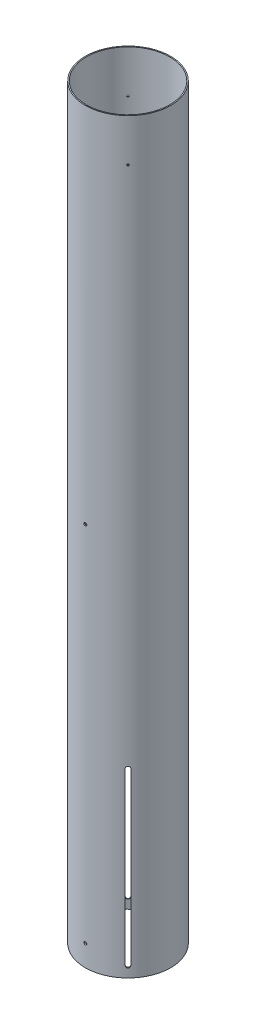
SolidWorks part; units mm, degrees
material "Wildman Fiberglass"
ref_plane "Front Plane" through (0, 0, 0) normal (0, 0, 1) x (1, 0, 0)
ref_plane "Top Plane" through (0, 0, 0) normal (0, 1, 0) x (1, 0, 0)
ref_plane "Right Plane" through (0, 0, 0) normal (1, 0, 0) x (0, 0, -1)
sketch "Sketch1" plane through (0, 0, 0) normal (0, 1, 0) x (1, 0, 0)
  circle A0 centre (0, 0) radius 49.53
  circle A1 centre (0, 0) radius 50.8
  dimension "D1" = 101.6
  dimension "D2" = 99.06
extrude "Boss-Extrude1" add sketch "Sketch1" along normal blind 889
extrude "Cut-Extrude1" cut sketch "Sketch2" against normal blind 152.4
sketch "Sketch2" plane through (14.4921, 1243.3556, -192.6285) normal (0.7071, 0, -0.7071) x (0, 1, 0)
  line L0 (-1230.6556, 128.3427) -> (-1027.4556, 128.3427)
  line L1 (-1027.4556, 123.5802) -> (-1230.6556, 123.5802)
  arc A0 (-1230.6556, 128.3427) -> (-1230.6556, 123.5802) centre (-1230.6556, 125.9615) ccw
  arc A1 (-1027.4556, 128.3427) -> (-1027.4556, 123.5802) centre (-1027.4556, 125.9615) cw
pattern_circular "CirPattern1" count 4 over 360 about axis through (0, 0, 0) along (0, 1, 0) of "Cut-Extrude1"
extrude "Cut-Extrude2" cut sketch "Sketch3" against normal blind 11.684
sketch "Sketch3" plane through (271.0916, 1243.3556, 52.3875) normal (0, 0, 1) x (-1, 0, 0)
  circle A0 centre (271.0916, 1217.9556) radius 1.7653
  circle A2 centre (271.0916, 786.1556) radius 1.7653
extrude "Cut-Extrude3" cut sketch "Sketch4" against normal blind 25.4
sketch "Sketch4" plane through (120.5803, 708.4046, -48.7382) normal (0.7071, 0, 0.7071) x (-0.7071, 0, 0.7071)
  line L0 (68.9263, -129.7954) -> (170.5263, -129.7954) construction
  circle A0 centre (119.7263, -129.7954) radius 1.0922
pattern_circular "CirPattern2" count 2 over 360 about axis through (0, 838.2, 0) along (0.7071, 0, 0.7071) of "Cut-Extrude3"
equation "\"Length\"=35"
equation "\"D1@Boss-Extrude1\"=\"Length\""
